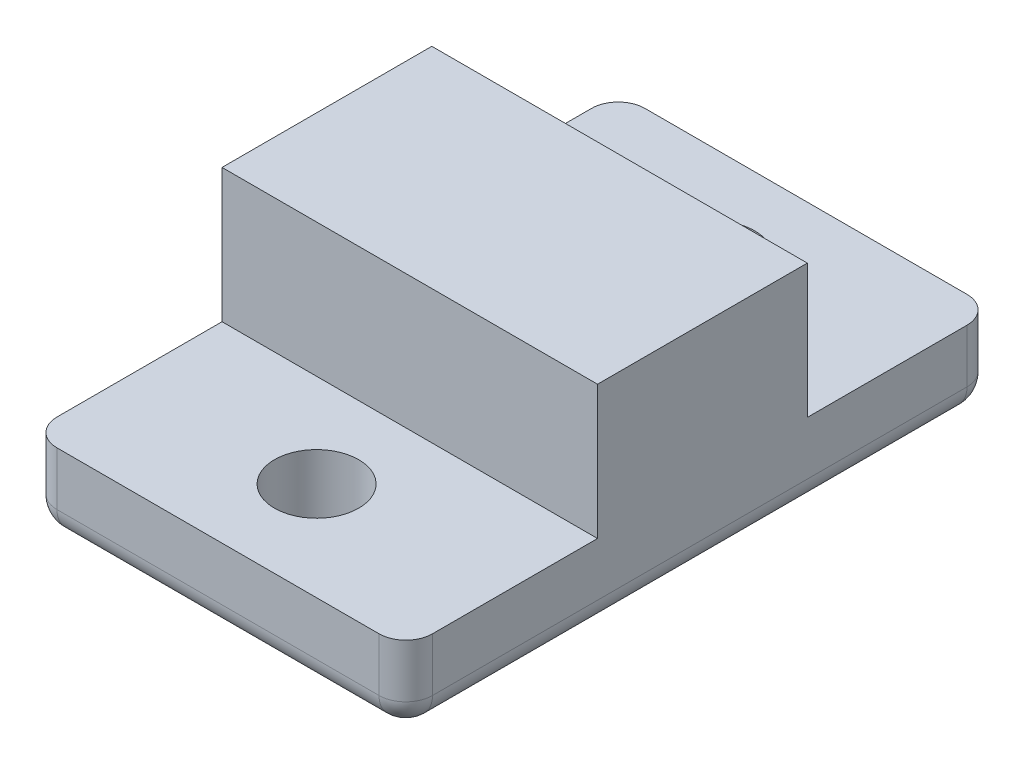
SolidWorks part; units mm, degrees
ref_plane "前视基准面" through (0, 0, 0) normal (0, 0, 1) x (1, 0, 0)
ref_plane "上视基准面" through (0, 0, 0) normal (0, 1, 0) x (1, 0, 0)
ref_plane "右视基准面" through (0, 0, 0) normal (1, 0, 0) x (0, 0, -1)
sketch "草图1" plane through (0, 0, 0) normal (0, 1, 0) x (1, 0, 0)
  line L1 (-7.025, 3.925) -> (7.025, 3.925)
  line L2 (-7.025, 3.925) -> (-7.025, -3.925)
  line L3 (-7.025, -3.925) -> (7.025, -3.925)
  line L4 (7.025, 3.925) -> (7.025, -3.925)
  line L5 (-7.025, 3.925) -> (7.025, -3.925) construction
  line L6 (-7.025, -3.925) -> (7.025, 3.925) construction
  point P0 (0, 0)
  dimension "D1" = 14.05
  dimension "D2" = 7.85
extrude "凸台-拉伸1" add sketch "草图1" along normal blind 5
ref_plane "基准面1" through (0, 0, 0) normal (0, -1, 0) x (-1, 0, 0)
sketch "草图2" plane through (0, 0, 0) normal (0, -1, 0) x (-1, 0, 0)
  line L0 (-7.025, 3.925) -> (-7.025, 10.9)
  line L1 (7.025, 3.925) -> (7.025, 10.9)
  line L2 (7.025, 10.9) -> (-7.025, 10.9)
  line L3 (-7.025, 3.925) -> (-7.025, -11.1)
  line L4 (-7.025, -11.1) -> (7.025, -11.1)
  line L5 (7.025, -11.1) -> (7.025, 3.925)
extrude "凸台-拉伸2" add sketch "草图2" along normal blind 3
ref_plane "基准面2" through (0, 0, 0) normal (0, 1, 0) x (1, 0, 0)
sketch "草图3" plane through (0, 0, 0) normal (0, 1, 0) x (1, 0, 0)
  line L0 (0, 10.9) -> (0, 3.925)
  line L1 (-7.025, 10.9) -> (7.025, 10.9) construction
  line L2 (7.025, 3.925) -> (-7.025, 3.925) construction
  line L3 (-7.025, 7.4125) -> (7.025, 7.4125)
  line L4 (-7.025, 3.925) -> (-7.025, 10.9) construction
  line L5 (7.025, 10.9) -> (7.025, 3.925) construction
  circle A0 centre (0, 7.4125) radius 1.575
extrude "切除-拉伸1" cut sketch "草图3" against normal blind 3 contours A0
mirror "镜向1" about plane through (0, 0, 0) normal (0, 0, 1) of "切除-拉伸1"
fillet "圆角2" radius 1 8 edges at (-7.025, -1.5, 11.1) (7.025, -1.5, 11.1) (7.025, -1.5, -10.9) (-7.025, -1.5, -10.9) (-7.025, -3, 0.1) (0, -3, 11.1) (7.025, -3, 0.1) (0, -3, -10.9)
